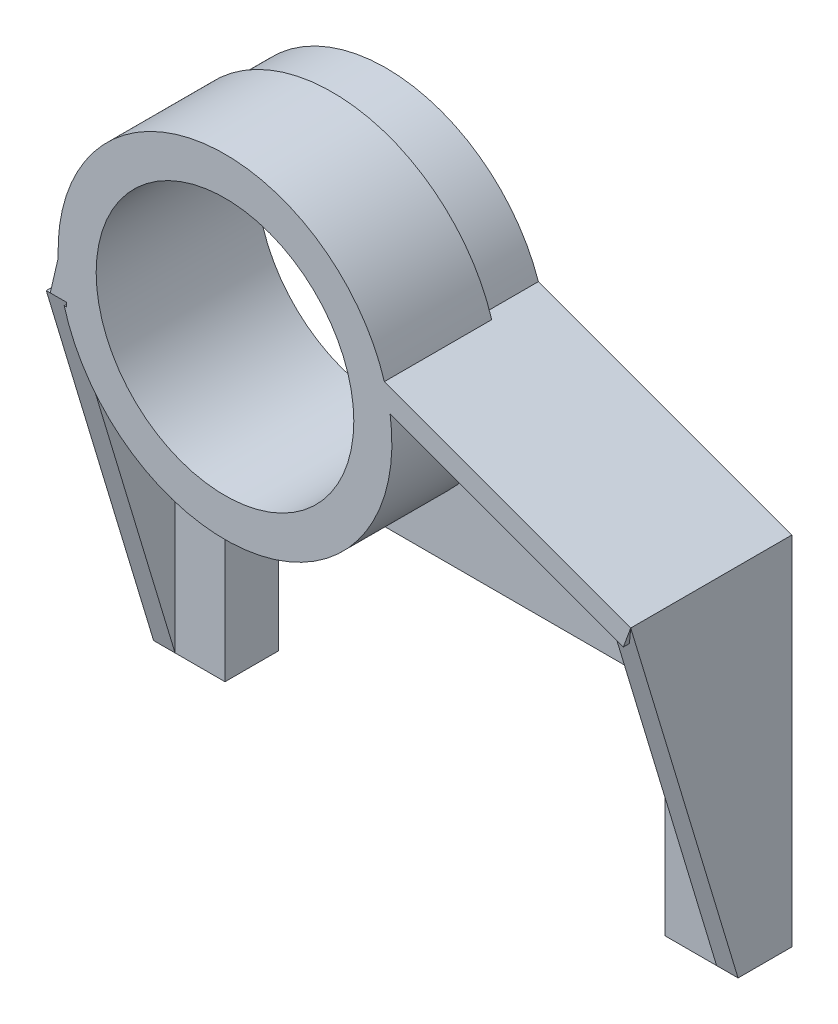
SolidWorks part; units mm, degrees
ref_plane "Front Plane" through (0, 0, 0) normal (0, 0, 1) x (1, 0, 0)
ref_plane "Top Plane" through (0, 0, 0) normal (0, 1, 0) x (1, 0, 0)
ref_plane "Right Plane" through (0, 0, 0) normal (1, 0, 0) x (0, 0, -1)
sketch "Sketch1" plane through (0, 0, 0) normal (0, 0, 1) x (1, 0, 0)
  line L0 (-27.15, 21.6665) -> (-25.112, 30.4522)
  line L1 (-27.15, -9.9552) -> (-20.5, -9.9552)
  line L2 (-27.15, -9.9552) -> (-27.15, 10)
  line L4 (-20.5, -9.9552) -> (-20.5, 10)
  line L5 (27.2933, -9.9552) -> (20.4977, -9.9552)
  line L6 (27.2933, -9.9552) -> (27.2933, 10)
  line L8 (20.4977, -9.9552) -> (20.4977, 10)
  line L9 (20.4977, 10) -> (-20.5, 10)
  line L10 (27.2933, 10) -> (27.2933, 23.2781)
  line L12 (-27.15, 10) -> (-27.15, 21.6665)
  line L14 (3.6918, 31.92) -> (27.2933, 23.2781)
  circle A0 centre (-10.5, 27.0627) radius 12 construction
  circle A1 centre (-10.5, 27.0627) radius 12
  arc A2 (3.6918, 31.92) -> (-25.112, 30.4522) centre (-10.5, 27.0627) ccw
  dimension "D1" = 30
extrude "Boss-Extrude1" add sketch "Sketch1" along normal blind 5
sketch "Sketch2" plane through (27.2933, 0, 0) normal (1, 0, 0) x (0, 0, -1)
  line L0 (-5, -9.9552) -> (-5, 23.2781)
  line L1 (-5, 23.2781) -> (-15, 23.2781)
  line L2 (-15, 23.2781) -> (-5, -9.9552)
  dimension "D1" = 10
extrude "Boss-Extrude2" add sketch "Sketch2" against normal blind 2
sketch "Sketch3" plane through (-27.15, 0, 0) normal (-1, 0, 0) x (0, 0, 1)
  line L0 (5, -9.9552) -> (5, 23.2781)
  line L1 (5, 23.2781) -> (15, 23.2781)
  line L2 (15, 23.2781) -> (5, -9.9552)
extrude "Boss-Extrude3" add sketch "Sketch3" against normal blind 2
sketch "Sketch4" plane through (0, 0, 5) normal (0, 0, 1) x (1, 0, 0)
  circle A0 centre (-10.5, 27.0627) radius 12 construction
  circle A1 centre (-10.5, 27.0627) radius 12
  circle A2 centre (-10.5, 27.0627) radius 15.5478
extrude "Boss-Extrude4" add sketch "Sketch4" along normal blind 10
sketch "Sketch5" plane through (-30.533, 7.0826, 0) normal (-0.9741, 0.226, 0) x (0, 0, 1)
  line L0 (5, 16.5411) -> (5, 25.56)
  line L1 (5, 25.56) -> (15, 25.56)
  line L2 (15, 8.4424) -> (15, 39.5379) construction
  line L3 (15, 25.56) -> (15, 16.5411)
  line L4 (15, 16.5411) -> (5, 16.5411)
extrude "Boss-Extrude5" add sketch "Sketch5" against normal blind 2
sketch "Sketch6" plane through (10.7425, 29.3383, 0) normal (0.3438, 0.939, 0) x (0.939, -0.3438, 0)
  line L1 (17.6254, -15) -> (-7.5183, -15)
  line L2 (17.6254, -15) -> (17.6254, -5)
  line L3 (17.6254, -5) -> (-7.5183, -5)
  line L4 (-7.5183, -15) -> (-7.5183, -5)
extrude "Boss-Extrude6" add sketch "Sketch6" against normal blind 2
sketch "Sketch7" plane through (3.7377, 16.1132, 0) normal (-0.226, -0.9741, 0) x (0.9741, -0.226, 0)
  line L3 (-29.9908, 15) -> (-31.3436, 15)
  line L4 (-31.3436, 14.9752) -> (-29.9908, 14.8833)
  line L5 (-31.3436, 15) -> (-31.3436, 14.9752)
  line L6 (-29.9908, 15) -> (-31.3436, 15)
  line L7 (-31.3436, 14.9752) -> (-29.9908, 14.8833)
  line L10 (-31.3436, 15) -> (-31.3436, 14.9752)
  line L11 (-29.9908, 14.8833) -> (-29.9908, 15)
  line L12 (-29.9908, 14.8833) -> (-29.9908, 15)
  dimension "D1" = 0
extrude "Cut-Extrude1" cut sketch "Sketch7" along direction (0, 0.9576, 0.2881) on the side against the normal blind 2
sketch "Sketch8" plane through (-25.4774, 0, 0) normal (-1, 0, 0) x (0, 0, 1)
  line L3 (15, 22.8901) -> (15, 23.2781)
  line L4 (15, 23.2781) -> (14.8833, 22.8901)
  line L5 (14.8833, 22.8901) -> (15, 22.8901)
  line L6 (15, 22.8901) -> (15, 23.2781)
  line L7 (15, 23.2781) -> (14.8833, 22.8901)
  line L9 (14.8833, 22.8901) -> (15, 22.8901)
  dimension "D1" = 0
extrude "Cut-Extrude2" cut sketch "Sketch8" along direction (-1, 0, 0) on the side against the normal blind 0.2
